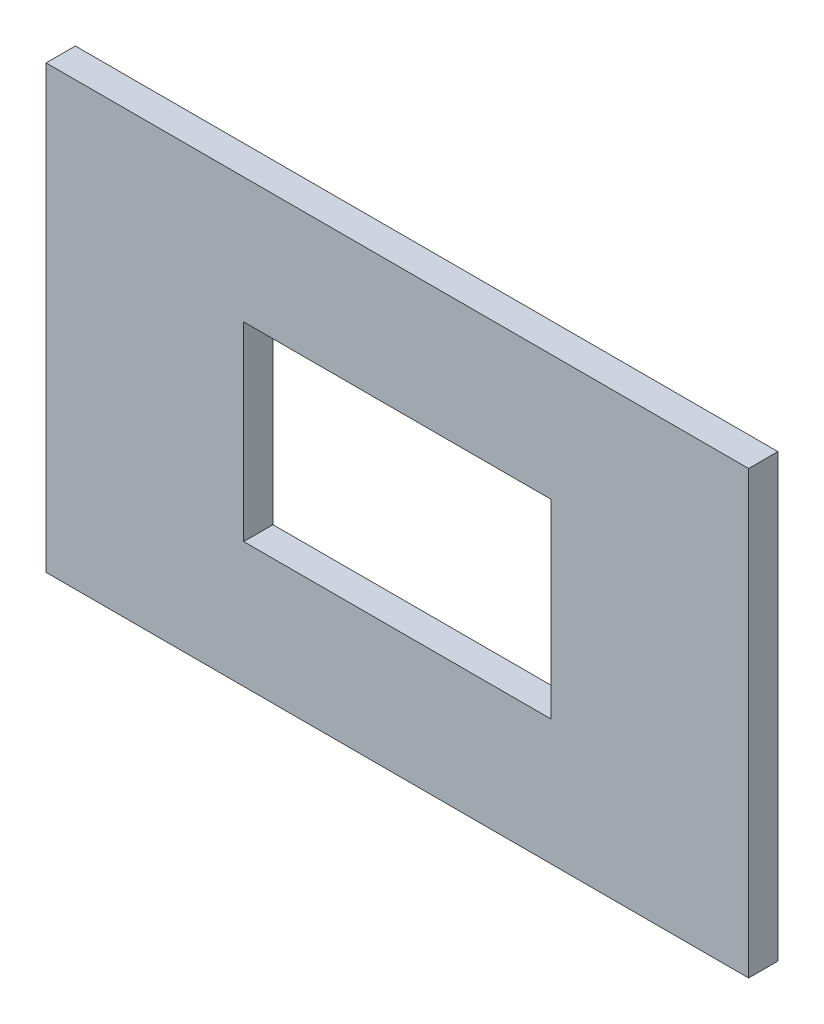
SolidWorks part; units mm, degrees
ref_plane "Alzado" through (0, 0, 0) normal (0, 0, 1) x (1, 0, 0)
ref_plane "Planta" through (0, 0, 0) normal (0, 1, 0) x (1, 0, 0)
ref_plane "Vista lateral" through (0, 0, 0) normal (1, 0, 0) x (0, 0, -1)
sketch "Croquis1" plane through (0, 0, 0) normal (0, 0, 1) x (1, 0, 0)
  line L0 (120, 0) -> (120, 150.7299) construction
  line L1 (0, 0) -> (240, 0)
  line L2 (0, 0) -> (0, 150.7299)
  line L3 (0, 150.7299) -> (240, 150.7299)
  line L4 (240, 0) -> (240, 150.7299)
  line L5 (120, 75.365) -> (240, 75.365) construction
  line L6 (120, 75.365) -> (67.5, 75.365) construction
  line L7 (67.5, 75.365) -> (67.5, 107.865) construction
  line L8 (67.5, 42.865) -> (67.5, 107.865)
  line L9 (67.5, 107.865) -> (172.5, 107.865)
  line L10 (67.5, 42.865) -> (172.5, 42.865)
  line L11 (172.5, 42.865) -> (172.5, 107.865)
  point P15 (120, 107.865)
  point P16 (120, 42.865)
extrude "Saliente-Extruir1" add sketch "Croquis1" along normal blind 10
